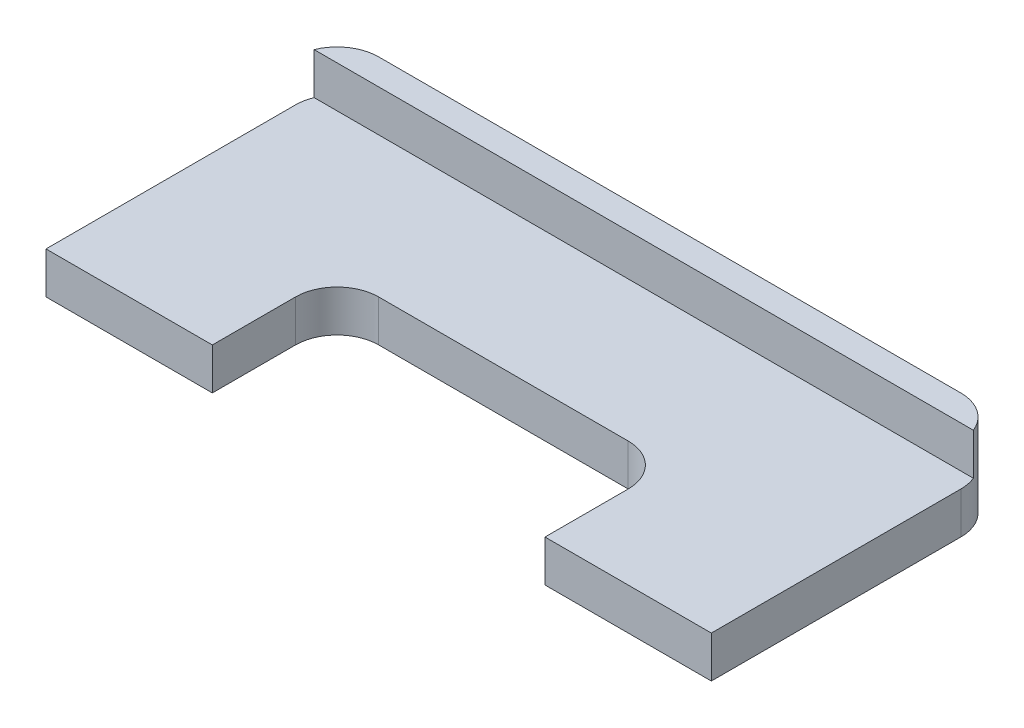
SolidWorks part; units mm, degrees
ref_plane "Front Plane" through (0, 0, 0) normal (0, 0, 1) x (1, 0, 0)
ref_plane "Top Plane" through (0, 0, 0) normal (0, 1, 0) x (1, 0, 0)
ref_plane "Right Plane" through (0, 0, 0) normal (1, 0, 0) x (0, 0, -1)
sketch "Sketch1" plane through (0, 0, 0) normal (0, 1, 0) x (1, 0, 0)
  line L1 (-10.16, -5.08) -> (10.16, -5.08)
  line L2 (-10.16, -5.08) -> (-10.16, 5.08)
  line L3 (-10.16, 5.08) -> (10.16, 5.08)
  line L4 (10.16, -5.08) -> (10.16, 5.08)
  line L5 (-10.16, -5.08) -> (10.16, 5.08) construction
  line L6 (-10.16, 5.08) -> (10.16, -5.08) construction
  point P0 (0, 0)
  dimension "D1" = 20.32
  dimension "D2" = 10.16
extrude "Boss-Extrude1" add sketch "Sketch1" along normal blind 1.27
sketch "Sketch2" plane through (0, 1.27, 0) normal (0, 1, 0) x (1, 0, 0)
  line L0 (-10.16, -5.08) -> (10.16, -5.08) construction
  line L1 (-5.08, -5.08) -> (5.08, -5.08)
  line L2 (-5.08, -5.08) -> (-5.08, 0)
  line L3 (-5.08, 0) -> (5.08, 0)
  line L4 (5.08, -5.08) -> (5.08, 0)
  point P6 (0, 0)
  dimension "D1" = 10.16
extrude "Cut-Extrude1" cut sketch "Sketch2" against normal through all
sketch "Sketch4" plane through (0, 1.27, 0) normal (0, 1, 0) x (1, 0, 0)
  line L0 (10.16, -5.08) -> (10.16, 5.08) construction
  line L1 (-10.16, 5.08) -> (10.16, 5.08)
  line L2 (-10.16, 5.08) -> (-10.16, 4.2862)
  line L3 (-10.16, 4.2862) -> (10.16, 4.2862)
  line L4 (10.16, 5.08) -> (10.16, 4.2862)
  dimension "D1" = 0.7937
extrude "Boss-Extrude2" add sketch "Sketch4" along normal blind 1.27
sketch "Sketch5" plane through (0, 0, 5.08) normal (0, 0, 1) x (1, 0, 0)
  line L0 (10.16, 1.27) -> (5.08, 1.27) construction
  line L1 (5.08, 1.27) -> (5.08, 0) construction
  line L2 (5.08, 0) -> (10.16, 0) construction
  line L3 (10.16, 0) -> (10.16, 1.27) construction
  line L4 (-10.16, 0) -> (-5.08, 0) construction
  line L5 (-5.08, 0) -> (-5.08, 1.27) construction
  line L6 (-5.08, 1.27) -> (-10.16, 1.27) construction
  line L7 (-10.16, 1.27) -> (-10.16, 0) construction
  line L8 (10.16, 1.27) -> (5.08, 1.27)
  line L9 (5.08, 1.27) -> (5.08, 0)
  line L10 (5.08, 0) -> (10.16, 0)
  line L11 (10.16, 0) -> (10.16, 1.27)
  line L12 (-10.16, 0) -> (-5.08, 0)
  line L13 (-5.08, 0) -> (-5.08, 1.27)
  line L14 (-5.08, 1.27) -> (-10.16, 1.27)
  line L15 (-10.16, 1.27) -> (-10.16, 0)
extrude "Cut-Extrude2" cut sketch "Sketch5" against normal blind 1.27
fillet "Fillet1" radius 1.27 4 edges at (10.16, 1.27, -5.08) (5.08, 0.635, 0) (-5.08, 0.635, 0) (-10.16, 1.27, -5.08)
